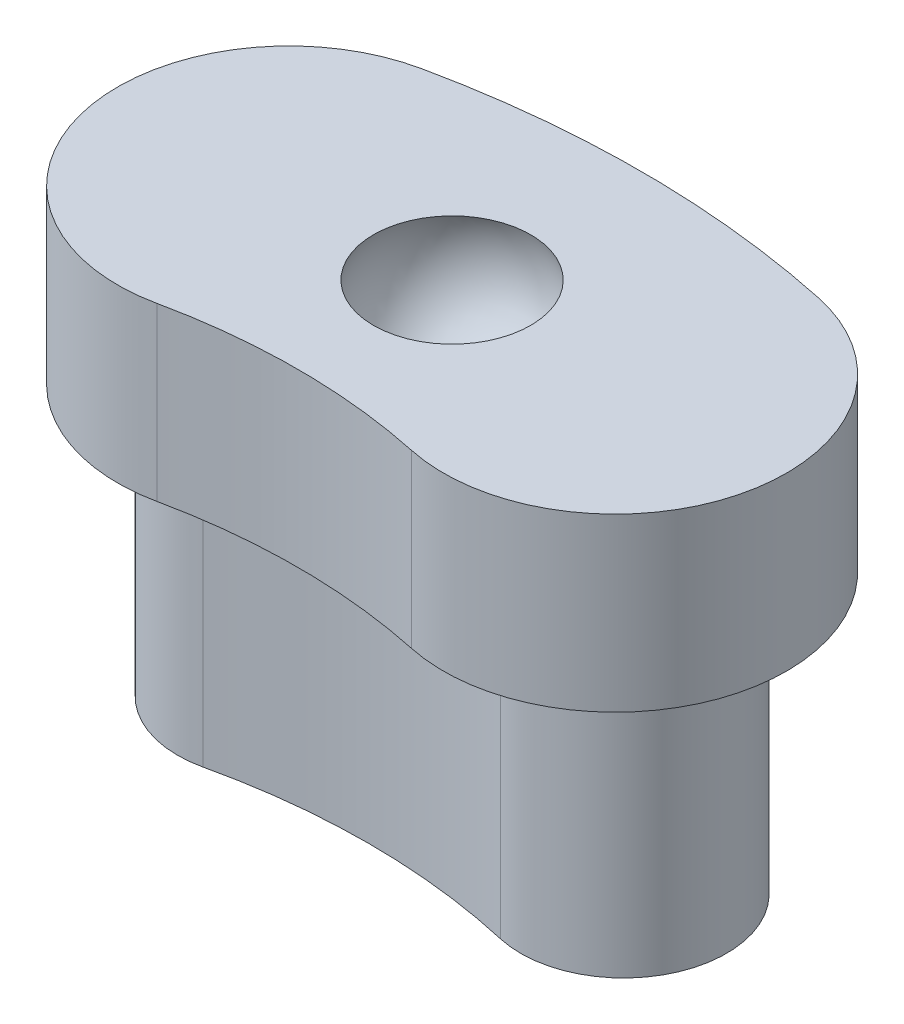
SolidWorks part; units mm, degrees
ref_plane "Front Plane" through (0, 0, 0) normal (0, 0, 1) x (1, 0, 0)
ref_plane "Top Plane" through (0, 0, 0) normal (0, 1, 0) x (1, 0, 0)
ref_plane "Right Plane" through (0, 0, 0) normal (1, 0, 0) x (0, 0, -1)
sketch "Sketch5" plane through (0, 0, 0) normal (0, 1, 0) x (1, 0, 0)
  line L0 (-4.75, 0) -> (4.75, 0) construction
  circle A0 centre (4.75, 0) radius 2.375 construction
  circle A1 centre (-4.75, 0) radius 2.375 construction
  arc A2 (-4.75, 0) -> (4.75, 0) centre (0, -22.3125) cw construction
  arc A3 (5.7911, 4.8904) -> (-5.7911, 4.8904) centre (0, -22.3125) ccw
  arc A4 (3.7089, -4.8904) -> (-3.7089, -4.8904) centre (0, -22.3125) ccw
  arc A5 (3.7089, -4.8904) -> (5.7911, 4.8904) centre (4.75, 0) ccw
  arc A6 (-5.7911, 4.8904) -> (-3.7089, -4.8904) centre (-4.75, 0) ccw
  point P5 (0, 0)
  point P6 (0, 0.5)
  dimension "D1" = 4.75
  dimension "D2" = 9.5
  dimension "D3" = 0.5
extrude "Boss-Extrude2" add sketch "Sketch5" along normal blind 5
sketch "Sketch9" plane through (0, 0, 0) normal (0, -1, 0) x (1, 0, 0)
  line L2 (0, 4.5) -> (0, -5.5) construction
  arc A0 (-5, 0) -> (5, 0) centre (0, 21.9374) ccw construction
  arc A5 (-3.7089, 4.8904) -> (3.7089, 4.8904) centre (0, 22.3125) ccw construction
  arc A6 (-5.7911, -4.8904) -> (5.7911, -4.8904) centre (0, 22.3125) ccw construction
  arc A7 (-5.6667, -2.925) -> (5.6667, -2.925) centre (0, 21.9374) ccw
  arc A8 (-4.3333, 2.925) -> (4.3333, 2.925) centre (0, 21.9374) ccw
  arc A9 (-4.3333, 2.925) -> (-5.6667, -2.925) centre (-5, 0) ccw
  arc A10 (5.6667, -2.925) -> (4.3333, 2.925) centre (5, 0) ccw
  point P3 (0, -0.5626)
  dimension "D4" = 22.5
  dimension "D3" = 3
  dimension "D1" = 10
  dimension "D2" = 5
extrude "Boss-Extrude3" add sketch "Sketch9" along normal blind 8
ref_plane "Plane2" through (0, 4, 0) normal (0, 1, 0) x (1, 0, 0)
sketch "Sketch11" plane through (0, 4, 0) normal (0, 1, 0) x (1, 0, 0)
  line L0 (0, 2.5) -> (0, -2.5)
  arc A0 (0, 2.5) -> (0, -2.5) centre (0, 0) ccw
  dimension "D1" = 5
revolve "Cut-Revolve1" cut sketch "Sketch11" angle 360 about L0
